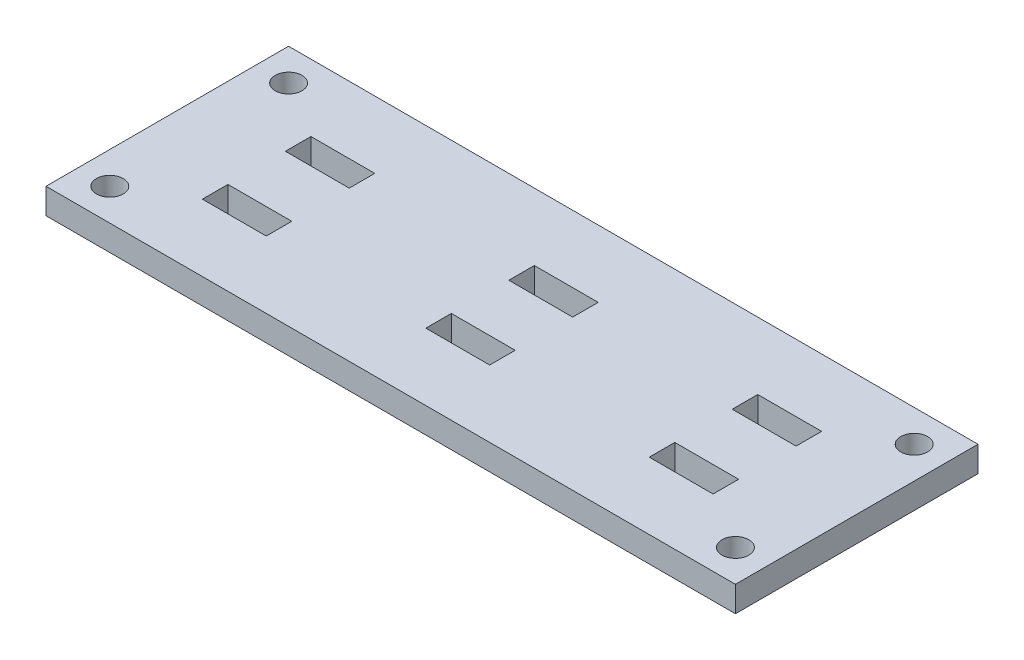
SolidWorks part; units mm, degrees
ref_plane "Front Plane" through (0, 0, 0) normal (0, 0, 1) x (1, 0, 0)
ref_plane "Top Plane" through (0, 0, 0) normal (0, 1, 0) x (1, 0, 0)
ref_plane "Right Plane" through (0, 0, 0) normal (1, 0, 0) x (0, 0, -1)
sketch "Sketch1" plane through (0, 0, 0) normal (0, 1, 0) x (1, 0, 0)
  line L0 (19, 14.5) -> (19, 23.5) construction
  line L1 (0, 38) -> (108, 38)
  line L2 (0, 38) -> (0, 0)
  line L3 (0, 0) -> (108, 0)
  line L4 (108, 38) -> (108, 0)
  line L5 (14, 14.5) -> (24, 14.5)
  line L6 (14, 14.5) -> (14, 10.5)
  line L7 (14, 10.5) -> (24, 10.5)
  line L8 (24, 14.5) -> (24, 10.5)
  line L9 (14, 23.5) -> (24, 23.5)
  line L10 (14, 23.5) -> (14, 27.5)
  line L11 (14, 27.5) -> (24, 27.5)
  line L12 (24, 23.5) -> (24, 27.5)
  line L29 (49, 23.5) -> (49, 27.5)
  line L30 (49, 23.5) -> (59, 23.5)
  line L31 (59, 23.5) -> (59, 27.5)
  line L32 (49, 27.5) -> (59, 27.5)
  line L33 (49, 14.5) -> (49, 10.5)
  line L34 (49, 14.5) -> (59, 14.5)
  line L35 (59, 14.5) -> (59, 10.5)
  line L36 (49, 10.5) -> (59, 10.5)
  line L37 (84, 23.5) -> (84, 27.5)
  line L38 (84, 23.5) -> (94, 23.5)
  line L39 (94, 23.5) -> (94, 27.5)
  line L40 (84, 27.5) -> (94, 27.5)
  line L41 (84, 14.5) -> (84, 10.5)
  line L42 (84, 14.5) -> (94, 14.5)
  line L43 (94, 14.5) -> (94, 10.5)
  line L44 (84, 10.5) -> (94, 10.5)
  circle A0 centre (5, 33) radius 2.1
  circle A1 centre (5, 5) radius 2.1
  circle A2 centre (103, 5) radius 2.1
  circle A3 centre (103, 33) radius 2.1
  point P23 (19, 19)
  dimension "D2" = 4.2
  dimension "D3" = 4.2
  dimension "D15" = 4.2
  dimension "D16" = 4.2
  dimension "D1" = 28
  dimension "D4" = 98
  dimension "D5" = 98
  dimension "D6" = 28
  dimension "D7" = 5
  dimension "D8" = 5
  dimension "D9" = 5
  dimension "D10" = 5
  dimension "D11" = 5
  dimension "D12" = 5
  dimension "D13" = 0
  dimension "D14" = 0
  dimension "D17" = 4
  dimension "D18" = 4
  dimension "D19" = 14
  dimension "D20" = 10
  dimension "D21" = 10
  dimension "D22" = 9
  dimension "D23" = 14
  dimension "D25" = 9
  dimension "D24" = 3
extrude "Boss-Extrude1" add sketch "Sketch1" along normal blind 4
